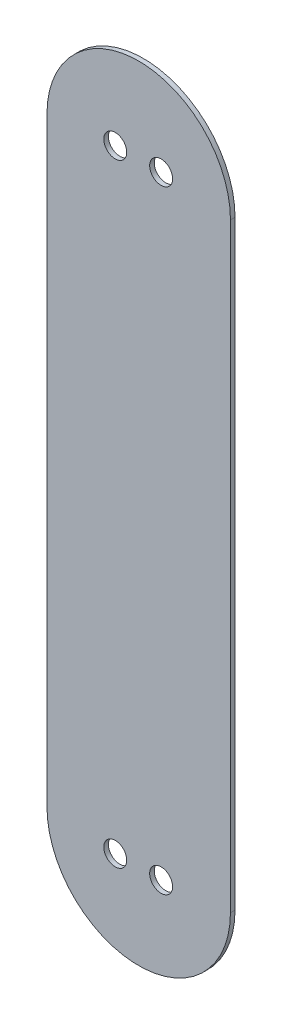
SolidWorks part; units mm, degrees
ref_plane "Front Plane" through (0, 0, 0) normal (0, 0, 1) x (1, 0, 0)
ref_plane "Top Plane" through (0, 0, 0) normal (0, 1, 0) x (1, 0, 0)
ref_plane "Right Plane" through (0, 0, 0) normal (1, 0, 0) x (0, 0, -1)
sketch "Sketch1" plane through (0, 0, 0) normal (0, 0, 1) x (1, 0, 0)
  line L0 (12.8, 329.894) -> (12.8, 199.1) construction
  line L1 (32.8, 329.894) -> (32.8, 199.1)
  line L2 (-7.2, 329.894) -> (-7.2, 199.1)
  arc A0 (32.8, 329.894) -> (-7.2, 329.894) centre (12.8, 329.894) ccw
  arc A1 (-7.2, 199.1) -> (32.8, 199.1) centre (12.8, 199.1) ccw
  circle A2 centre (17.6884, 331.341) radius 2.5
  circle A3 centre (7.6884, 331.341) radius 2.5
  circle A4 centre (17.6884, 197.7) radius 2.5
  circle A5 centre (7.6884, 197.7) radius 2.5
  point P2 (12.8, 264.497)
  dimension "D2" = 5
  dimension "D3" = 5
  dimension "D4" = 10
  dimension "D5" = 5
  dimension "D6" = 5
  dimension "D1" = 40
extrude "Boss-Extrude1" add sketch "Sketch1" along normal blind 1
